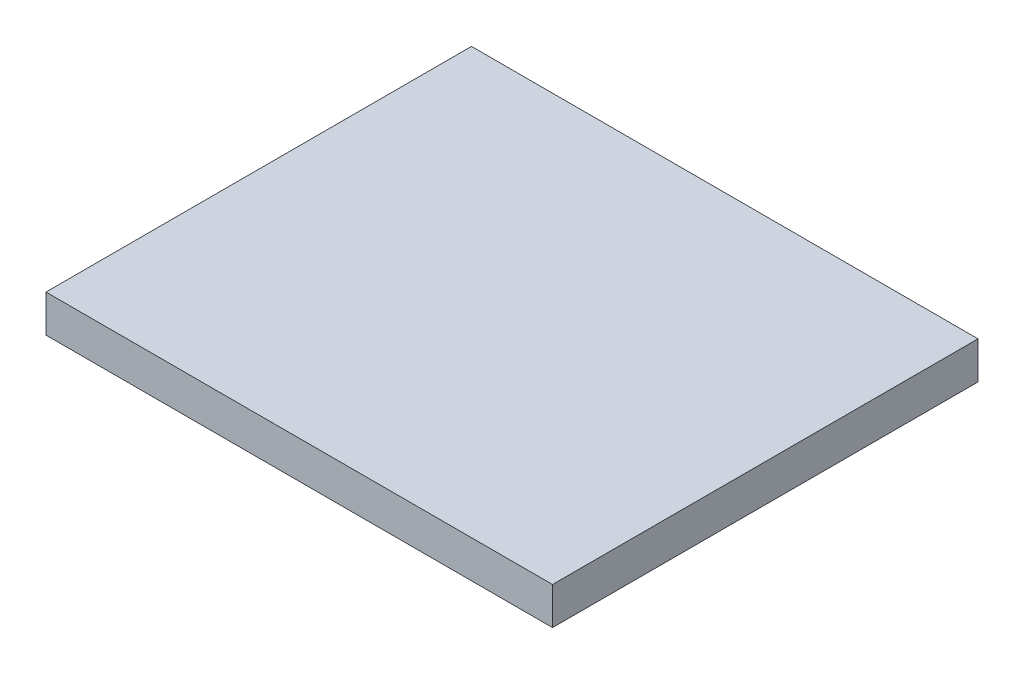
SolidWorks part; units mm, degrees
ref_plane "Front" through (0, 0, 0) normal (0, 0, 1) x (1, 0, 0)
ref_plane "Top" through (0, 0, 0) normal (0, 1, 0) x (1, 0, 0)
ref_plane "Right" through (0, 0, 0) normal (1, 0, 0) x (0, 0, -1)
sketch "Sketch1" plane through (0, 0, 0) normal (0, 1, 0) x (1, 0, 0)
  line L1 (-62.5, -52.5) -> (62.5, -52.5)
  line L2 (-62.5, -52.5) -> (-62.5, 52.5)
  line L3 (-62.5, 52.5) -> (62.5, 52.5)
  line L4 (62.5, -52.5) -> (62.5, 52.5)
  line L5 (-62.5, -52.5) -> (62.5, 52.5) construction
  line L6 (-62.5, 52.5) -> (62.5, -52.5) construction
  point P0 (0, 0)
  dimension "D1" = 125
  dimension "D2" = 105
extrude "Test_Base_Postion" add sketch "Sketch1" along normal blind 9.215
sketch "Thumb_Position" plane through (0, 9.215, 0) normal (0, 1, 0) x (1, 0, 0)
  line L0 (62.5, -52.5) -> (62.5, 52.5) construction
  line L1 (49, -12) -> (17, -12)
  line L2 (49, -12) -> (49, 43)
  line L3 (49, 43) -> (17, 43)
  line L4 (17, -12) -> (17, 43)
  line L5 (33, 43) -> (33, -12) construction
  line L6 (51, -12) -> (15, -12)
  line L7 (51, -12) -> (51, 12)
  line L8 (51, 12) -> (15, 12)
  line L9 (15, -12) -> (15, 12)
  line L10 (33, 12) -> (33, -12) construction
  line L12 (51, 0) -> (15, 0) construction
  circle A1 centre (42, 0) radius 9
  circle A2 centre (42, 0) radius 17.75 construction
  dimension "D6" = 18
  dimension "D7" = 20.5
  dimension "D5" = 35.5
  dimension "D1" = 55
  dimension "D2" = 32
  dimension "D3" = 36
  dimension "D4" = 24
sketch "Finger_Gears_Position" plane through (0, 0, 0) normal (0, -1, 0) x (1, 0, 0)
  line L0 (-30, 32) -> (-30, 49.5) construction
  line L1 (-30, 32) -> (-47.5, 32) construction
  line L2 (-30, -32) -> (-30, -49.5) construction
  line L3 (-30, -32) -> (-47.5, -32) construction
  line L4 (-62.5, -52.5) -> (-62.5, 52.5) construction
  line L5 (-62.5, 52.5) -> (62.5, 52.5) construction
  line L8 (62.5, -52.5) -> (-62.5, -52.5) construction
  line L9 (-62.5, 0) -> (62.5, 0) construction
  line L10 (62.5, 52.5) -> (62.5, -52.5) construction
  line L13 (-30, -32) -> (-43, -32) construction
  line L15 (-43, -48) -> (12, -48) construction
  line L16 (-43, -48) -> (-43, -16) construction
  line L17 (-43, -16) -> (12, -16) construction
  line L18 (12, -48) -> (12, -16) construction
  line L20 (-30, 32) -> (-43, 32) construction
  line L21 (12, -32) -> (-23, -32) construction
  line L22 (-43, 16) -> (12, 16) construction
  line L23 (-43, 16) -> (-43, 48) construction
  line L24 (-43, 48) -> (12, 48) construction
  line L25 (12, 16) -> (12, 48) construction
  line L26 (12, 32) -> (-23, 32) construction
  line L27 (-23, -32) -> (-23, 32) construction
  circle A0 centre (-30, 32) radius 17.5 construction
  circle A1 centre (-30, -32) radius 17.5 construction
  dimension "D1" = 35
  dimension "D2" = 15
  dimension "D3" = 3
  dimension "D4" = 3
  dimension "D5" = 13
  dimension "D6" = 55
  dimension "D7" = 32
  dimension "D8" = 13
  dimension "D9" = 55
  dimension "D10" = 32
  dimension "D11" = 35
  dimension "D12" = 35
sketch "Fingers_Position" plane through (0, 9.215, 0) normal (0, 1, 0) x (1, 0, 0)
  line L0 (12, 32) -> (-23, 32) construction
  line L1 (12, 16) -> (-43, 16)
  line L2 (12, 16) -> (12, 48)
  line L3 (12, 48) -> (-43, 48)
  line L4 (-43, 16) -> (-43, 48)
  line L5 (12, -48) -> (-43, -48)
  line L6 (12, -48) -> (12, -16)
  line L7 (12, -16) -> (-43, -16)
  line L8 (-43, -48) -> (-43, -16)
  line L9 (-23, 32) -> (-23, -32) construction
  line L10 (-23, -32) -> (12, -32) construction
sketch "Thumb_Knuckle_Mount_Position" plane through (0, 0, 0) normal (0, -1, 0) x (1, 0, 0)
  circle A0 centre (42, 0) radius 17.75
  dimension "D1" = 35.5
sketch "Gears_Position" plane through (0, 0, 0) normal (0, -1, 0) x (-1, 0, 0)
  line L0 (30, 32) -> (30, 13.5) construction
  line L1 (30, 32) -> (30.5905, 16.5113) construction
  line L2 (30.7851, 15.5187) -> (29.2149, 15.5187) construction
  line L3 (31.4977, 13.5607) -> (30, 17.6757) construction
  line L4 (28.2415, 13.5838) -> (30, 32) construction
  line L5 (29.2149, 15.5187) -> (27.6518, 15.6679) construction
  line L6 (30, -32) -> (30, -50.5) construction
  line L7 (30.7851, -48.4813) -> (29.2149, -48.4813) construction
  line L8 (30.5905, -47.4887) -> (30, -32) construction
  line L9 (31.4977, -50.4393) -> (30, -46.3243) construction
  line L10 (30, -32) -> (28.2415, -50.4162) construction
  line L11 (29.2149, -48.4813) -> (27.6518, -48.3321) construction
  line L12 (47.5, 2.2754) -> (47.5, -12.2246) construction
  line L13 (47.5, 2.2754) -> (48.0842, -9.2098) construction
  line L14 (48.2849, -10.1999) -> (46.7151, -10.1999) construction
  line L15 (48.9937, -12.1475) -> (47.5, -8.0435) construction
  line L16 (47.5, 2.2754) -> (45.6827, -12.1103) construction
  line L17 (46.7151, -10.1999) -> (45.1577, -10.0032) construction
  line L18 (19.3829, -13.0418) -> (17.8132, -13.0418) construction
  line L19 (18.5981, -0.5664) -> (16.7807, -14.9521) construction
  line L20 (17.8132, -13.0418) -> (16.2558, -12.845) construction
  line L21 (18.5981, -0.5664) -> (18.5981, -15.0664) construction
  line L22 (18.5981, -0.5664) -> (19.1823, -12.0516) construction
  line L23 (20.0918, -14.9893) -> (18.5981, -10.8853) construction
  line L24 (-8.6772, -11.927) -> (33.5, -2.2788) construction
  line L25 (16.0694, 14.2189) -> (8.7534, -28.4247) construction
  line L26 (-8.6772, -11.927) -> (16.0694, 14.2189) construction
  line L27 (-8.6772, -11.927) -> (8.7534, -28.4247) construction
  line L28 (8.7534, -28.4247) -> (33.5, -2.2788) construction
  line L29 (16.0694, 14.2189) -> (33.5, -2.2788) construction
  line L30 (12.4114, -7.1029) -> (24.7847, 5.97) construction
  line L31 (62.5, 52.5) -> (62.5, -52.5) construction
  circle A0 centre (30, -32) radius 17.5 construction
  circle A1 centre (30, 32) radius 17.5 construction
  circle A2 centre (30, 32) radius 16.5
  circle A3 centre (30, 32) radius 15.5 construction
  circle A4 centre (30, 32) radius 18.5 construction
  arc A5 (32.4899, 13.6683) -> (30.5905, 16.5113) centre (33.854, 16.6357) cw
  arc A6 (27.5101, 13.6683) -> (29.4095, 16.5113) centre (26.146, 16.6357) ccw
  arc A7 (32.4899, -50.3317) -> (30.5905, -47.4887) centre (33.854, -47.3643) cw
  arc A8 (27.5101, -50.3317) -> (29.4095, -47.4887) centre (26.146, -47.3643) ccw
  circle A9 centre (30, -32) radius 16.5
  circle A10 centre (30, -32) radius 18.5 construction
  circle A11 centre (30, -32) radius 15.5 construction
  arc A12 (28.9757, -50.4716) -> (27.6486, -47.3206) centre (30.8766, -47.816) cw
  arc A13 (24.0858, -49.5292) -> (26.4889, -47.0971) centre (23.3079, -46.3573) ccw
  arc A14 (25.4984, -49.944) -> (24.7916, -46.5987) centre (27.8676, -47.6961) cw
  arc A15 (20.8752, -48.0931) -> (23.6952, -46.1598) centre (20.7117, -44.8314) ccw
  arc A16 (22.1838, -48.7678) -> (22.1229, -45.3492) centre (24.9356, -47.0089) cw
  arc A17 (17.9945, -46.0754) -> (21.1294, -44.7107) centre (18.4512, -42.8417) ccw
  arc A18 (19.1518, -46.9855) -> (19.7389, -43.6172) centre (22.1867, -45.7792) cw
  arc A19 (15.5476, -43.549) -> (18.8842, -42.8022) centre (16.6081, -40.4601) ccw
  arc A20 (16.5118, -44.6617) -> (17.7258, -41.4654) centre (19.7201, -44.0516) cw
  arc A21 (13.6232, -40.6052) -> (17.0407, -40.5033) centre (15.2491, -37.7728) ccw
  arc A22 (14.3593, -41.8802) -> (16.1562, -38.9714) centre (17.6251, -41.8883) cw
  arc A23 (12.2906, -37.3503) -> (15.6656, -37.8971) centre (14.4231, -34.8769) ccw
  arc A24 (12.7721, -38.7416) -> (15.0871, -36.2255) centre (15.9774, -39.3676) cw
  arc A25 (11.598, -33.9021) -> (14.8086, -35.0777) centre (14.1602, -31.8769) ccw
  arc A26 (11.8076, -35.3594) -> (14.5569, -33.3268) centre (14.8365, -36.5807) cw
  arc A27 (11.5706, -30.3851) -> (14.5007, -32.1471) centre (14.4697, -28.8814) ccw
  arc A28 (11.5006, -31.8557) -> (14.5849, -30.3802) centre (14.2436, -33.6282) cw
  arc A29 (12.2093, -26.9265) -> (14.7529, -29.2112) centre (15.3405, -25.9987) ccw
  arc A30 (11.8622, -28.3573) -> (15.17, -27.4922) centre (14.2202, -30.6169) cw
  arc A31 (13.4909, -23.6513) -> (15.5563, -26.3761) centre (16.7412, -23.3328) ccw
  arc A32 (12.8793, -24.9905) -> (16.2911, -24.767) centre (14.7671, -27.6555) cw
  arc A33 (15.3693, -20.6778) -> (16.8816, -23.7442) centre (18.6211, -20.9802) ccw
  arc A34 (14.5153, -21.8771) -> (17.9077, -22.3033) centre (15.8646, -24.8512) cw
  arc A35 (17.7764, -18.1135) -> (18.6811, -21.4107) centre (20.9122, -19.0259) ccw
  arc A36 (16.7109, -19.1295) -> (19.9613, -20.1901) centre (17.473, -22.3052) cw
  arc A37 (20.6253, -16.0511) -> (20.8897, -19.46) centre (23.5318, -17.5404) ccw
  arc A38 (19.3868, -16.8471) -> (22.3778, -18.5036) centre (19.5341, -20.1096) cw
  arc A39 (23.8131, -14.5652) -> (23.4275, -17.9625) centre (26.3852, -16.5776) ccw
  arc A40 (22.4463, -15.1124) -> (25.0697, -17.305) centre (21.9735, -18.3438) cw
  arc A41 (27.2245, -13.7094) -> (26.2029, -16.9723) centre (29.3693, -16.1722) ccw
  arc A42 (25.7788, -13.988) -> (27.9399, -16.6375) centre (24.703, -17.0716) cw
  arc A43 (30.7361, -13.5147) -> (29.1155, -16.5253) centre (32.3761, -16.3389) ccw
  arc A44 (29.2639, -13.5147) -> (30.8845, -16.5253) centre (27.6239, -16.3389) cw
  arc A45 (34.2212, -13.988) -> (32.0601, -16.6375) centre (35.297, -17.0716) ccw
  arc A46 (32.7755, -13.7094) -> (33.7971, -16.9723) centre (30.6307, -16.1722) cw
  arc A47 (37.5537, -15.1124) -> (34.9303, -17.305) centre (38.0265, -18.3438) ccw
  arc A48 (36.1869, -14.5652) -> (36.5725, -17.9625) centre (33.6148, -16.5776) cw
  arc A49 (40.6132, -16.8471) -> (37.6222, -18.5036) centre (40.4659, -20.1096) ccw
  arc A50 (39.3747, -16.0511) -> (39.1103, -19.46) centre (36.4682, -17.5404) cw
  arc A51 (43.2891, -19.1295) -> (40.0387, -20.1901) centre (42.527, -22.3052) ccw
  arc A52 (42.2236, -18.1135) -> (41.3189, -21.4107) centre (39.0878, -19.0259) cw
  arc A53 (45.4847, -21.8771) -> (42.0923, -22.3033) centre (44.1354, -24.8512) ccw
  arc A54 (44.6307, -20.6778) -> (43.1184, -23.7442) centre (41.3789, -20.9802) cw
  arc A55 (47.1207, -24.9905) -> (43.7089, -24.767) centre (45.2329, -27.6555) ccw
  arc A56 (46.5091, -23.6513) -> (44.4437, -26.3761) centre (43.2588, -23.3328) cw
  arc A57 (48.1378, -28.3573) -> (44.83, -27.4922) centre (45.7798, -30.6169) ccw
  arc A58 (47.7907, -26.9265) -> (45.2471, -29.2112) centre (44.6595, -25.9987) cw
  arc A59 (48.4994, -31.8557) -> (45.4151, -30.3802) centre (45.7564, -33.6282) ccw
  arc A60 (48.4294, -30.3851) -> (45.4993, -32.1471) centre (45.5303, -28.8814) cw
  arc A61 (48.1924, -35.3594) -> (45.4431, -33.3268) centre (45.1635, -36.5807) ccw
  arc A62 (48.402, -33.9021) -> (45.1914, -35.0777) centre (45.8398, -31.8769) cw
  arc A63 (47.2279, -38.7416) -> (44.9129, -36.2255) centre (44.0226, -39.3676) ccw
  arc A64 (47.7094, -37.3503) -> (44.3344, -37.8971) centre (45.5769, -34.8769) cw
  arc A65 (45.6407, -41.8802) -> (43.8438, -38.9714) centre (42.3749, -41.8883) ccw
  arc A66 (46.3768, -40.6052) -> (42.9593, -40.5033) centre (44.7509, -37.7728) cw
  arc A67 (43.4882, -44.6617) -> (42.2742, -41.4654) centre (40.2799, -44.0516) ccw
  arc A68 (44.4524, -43.549) -> (41.1158, -42.8022) centre (43.3919, -40.4601) cw
  arc A69 (40.8482, -46.9855) -> (40.2611, -43.6172) centre (37.8133, -45.7792) ccw
  arc A70 (42.0055, -46.0754) -> (38.8706, -44.7107) centre (41.5488, -42.8417) cw
  arc A71 (37.8162, -48.7678) -> (37.8771, -45.3492) centre (35.0644, -47.0089) ccw
  arc A72 (39.1248, -48.0931) -> (36.3048, -46.1598) centre (39.2883, -44.8314) cw
  arc A73 (34.5016, -49.944) -> (35.2084, -46.5987) centre (32.1324, -47.6961) ccw
  arc A74 (35.9142, -49.5292) -> (33.5111, -47.0971) centre (36.6921, -46.3573) cw
  arc A75 (31.0243, -50.4716) -> (32.3514, -47.3206) centre (29.1234, -47.816) ccw
  arc A76 (28.9757, 13.5284) -> (27.6486, 16.6794) centre (30.8766, 16.184) cw
  arc A77 (24.0858, 14.4708) -> (26.4889, 16.9029) centre (23.3079, 17.6427) ccw
  arc A78 (25.4984, 14.056) -> (24.7916, 17.4013) centre (27.8676, 16.3039) cw
  arc A79 (20.8752, 15.9069) -> (23.6952, 17.8402) centre (20.7117, 19.1686) ccw
  arc A80 (22.1838, 15.2322) -> (22.1229, 18.6508) centre (24.9356, 16.9911) cw
  arc A81 (17.9945, 17.9246) -> (21.1294, 19.2893) centre (18.4512, 21.1583) ccw
  arc A82 (19.1518, 17.0145) -> (19.7389, 20.3828) centre (22.1867, 18.2208) cw
  arc A83 (15.5476, 20.451) -> (18.8842, 21.1978) centre (16.6081, 23.5399) ccw
  arc A84 (16.5118, 19.3383) -> (17.7258, 22.5346) centre (19.7201, 19.9484) cw
  arc A85 (13.6232, 23.3948) -> (17.0407, 23.4967) centre (15.2491, 26.2272) ccw
  arc A86 (14.3593, 22.1198) -> (16.1562, 25.0286) centre (17.6251, 22.1117) cw
  arc A87 (12.2906, 26.6497) -> (15.6656, 26.1029) centre (14.4231, 29.1231) ccw
  arc A88 (12.7721, 25.2584) -> (15.0871, 27.7745) centre (15.9774, 24.6324) cw
  arc A89 (11.598, 30.0979) -> (14.8086, 28.9223) centre (14.1602, 32.1231) ccw
  arc A90 (11.8076, 28.6406) -> (14.5569, 30.6732) centre (14.8365, 27.4193) cw
  arc A91 (11.5706, 33.6149) -> (14.5007, 31.8529) centre (14.4697, 35.1186) ccw
  arc A92 (11.5006, 32.1443) -> (14.5849, 33.6198) centre (14.2436, 30.3718) cw
  arc A93 (12.2093, 37.0735) -> (14.7529, 34.7888) centre (15.3405, 38.0013) ccw
  arc A94 (11.8622, 35.6427) -> (15.17, 36.5078) centre (14.2202, 33.3831) cw
  arc A95 (13.4909, 40.3487) -> (15.5563, 37.6239) centre (16.7412, 40.6672) ccw
  arc A96 (12.8793, 39.0095) -> (16.2911, 39.233) centre (14.7671, 36.3445) cw
  arc A97 (15.3693, 43.3222) -> (16.8816, 40.2558) centre (18.6211, 43.0198) ccw
  arc A98 (14.5153, 42.1229) -> (17.9077, 41.6967) centre (15.8646, 39.1488) cw
  arc A99 (17.7764, 45.8865) -> (18.6811, 42.5893) centre (20.9122, 44.9741) ccw
  arc A100 (16.7109, 44.8705) -> (19.9613, 43.8099) centre (17.473, 41.6948) cw
  arc A101 (20.6253, 47.9489) -> (20.8897, 44.54) centre (23.5318, 46.4596) ccw
  arc A102 (19.3868, 47.1529) -> (22.3778, 45.4964) centre (19.5341, 43.8904) cw
  arc A103 (23.8131, 49.4348) -> (23.4275, 46.0375) centre (26.3852, 47.4224) ccw
  arc A104 (22.4463, 48.8876) -> (25.0697, 46.695) centre (21.9735, 45.6562) cw
  arc A105 (27.2245, 50.2906) -> (26.2029, 47.0277) centre (29.3693, 47.8278) ccw
  arc A106 (25.7788, 50.012) -> (27.9399, 47.3625) centre (24.703, 46.9284) cw
  arc A107 (30.7361, 50.4853) -> (29.1155, 47.4747) centre (32.3761, 47.6611) ccw
  arc A108 (29.2639, 50.4853) -> (30.8845, 47.4747) centre (27.6239, 47.6611) cw
  arc A109 (34.2212, 50.012) -> (32.0601, 47.3625) centre (35.297, 46.9284) ccw
  arc A110 (32.7755, 50.2906) -> (33.7971, 47.0277) centre (30.6307, 47.8278) cw
  arc A111 (37.5537, 48.8876) -> (34.9303, 46.695) centre (38.0265, 45.6562) ccw
  arc A112 (36.1869, 49.4348) -> (36.5725, 46.0375) centre (33.6148, 47.4224) cw
  arc A113 (40.6132, 47.1529) -> (37.6222, 45.4964) centre (40.4659, 43.8904) ccw
  arc A114 (39.3747, 47.9489) -> (39.1103, 44.54) centre (36.4682, 46.4596) cw
  arc A115 (43.2891, 44.8705) -> (40.0387, 43.8099) centre (42.527, 41.6948) ccw
  arc A116 (42.2236, 45.8865) -> (41.3189, 42.5893) centre (39.0878, 44.9741) cw
  arc A117 (45.4847, 42.1229) -> (42.0923, 41.6967) centre (44.1354, 39.1488) ccw
  arc A118 (44.6307, 43.3222) -> (43.1184, 40.2558) centre (41.3789, 43.0198) cw
  arc A119 (47.1207, 39.0095) -> (43.7089, 39.233) centre (45.2329, 36.3445) ccw
  arc A120 (46.5091, 40.3487) -> (44.4437, 37.6239) centre (43.2588, 40.6672) cw
  arc A121 (48.1378, 35.6427) -> (44.83, 36.5078) centre (45.7798, 33.3831) ccw
  arc A122 (47.7907, 37.0735) -> (45.2471, 34.7888) centre (44.6595, 38.0013) cw
  arc A123 (48.4994, 32.1443) -> (45.4151, 33.6198) centre (45.7564, 30.3718) ccw
  arc A124 (48.4294, 33.6149) -> (45.4993, 31.8529) centre (45.5303, 35.1186) cw
  arc A125 (48.1924, 28.6406) -> (45.4431, 30.6732) centre (45.1635, 27.4193) ccw
  arc A126 (48.402, 30.0979) -> (45.1914, 28.9223) centre (45.8398, 32.1231) cw
  arc A127 (47.2279, 25.2584) -> (44.9129, 27.7745) centre (44.0226, 24.6324) ccw
  arc A128 (47.7094, 26.6497) -> (44.3344, 26.1029) centre (45.5769, 29.1231) cw
  arc A129 (45.6407, 22.1198) -> (43.8438, 25.0286) centre (42.3749, 22.1117) ccw
  arc A130 (46.3768, 23.3948) -> (42.9593, 23.4967) centre (44.7509, 26.2272) cw
  arc A131 (43.4882, 19.3383) -> (42.2742, 22.5346) centre (40.2799, 19.9484) ccw
  arc A132 (44.4524, 20.451) -> (41.1158, 21.1978) centre (43.3919, 23.5399) cw
  arc A133 (40.8482, 17.0145) -> (40.2611, 20.3828) centre (37.8133, 18.2208) ccw
  arc A134 (42.0055, 17.9246) -> (38.8706, 19.2893) centre (41.5488, 21.1583) cw
  arc A135 (37.8162, 15.2322) -> (37.8771, 18.6508) centre (35.0644, 16.9911) ccw
  arc A136 (39.1248, 15.9069) -> (36.3048, 17.8402) centre (39.2883, 19.1686) cw
  arc A137 (34.5016, 14.056) -> (35.2084, 17.4013) centre (32.1324, 16.3039) ccw
  arc A138 (35.9142, 14.4708) -> (33.5111, 16.9029) centre (36.6921, 17.6427) cw
  arc A139 (31.0243, 13.5284) -> (32.3514, 16.6794) centre (29.1234, 16.184) ccw
  circle A140 centre (47.5, 2.2754) radius 11.5 construction
  circle A141 centre (47.5, 2.2754) radius 12.5
  circle A142 centre (47.5, 2.2754) radius 13.5 construction
  circle A143 centre (47.5, 2.2754) radius 14.5 construction
  arc A144 (49.8668, -12.0301) -> (48.0842, -9.2098) centre (51.48, -9.037) cw
  arc A145 (45.1332, -12.0301) -> (46.9158, -9.2098) centre (43.52, -9.037) ccw
  arc A146 (16.2312, -14.872) -> (18.0138, -12.0516) centre (14.6181, -11.8789) ccw
  circle A147 centre (18.5981, -0.5664) radius 11.5 construction
  circle A148 centre (18.5981, -0.5664) radius 12.5
  arc A149 (20.9649, -14.872) -> (19.1823, -12.0516) centre (22.578, -11.8789) cw
  circle A150 centre (18.5981, -0.5664) radius 13.5 construction
  circle A151 centre (18.5981, -0.5664) radius 14.5 construction
  arc A152 (46.2348, -12.1693) -> (45.2096, -8.9942) centre (48.5416, -9.6714) cw
  arc A153 (41.6499, -10.9921) -> (44.0779, -8.7036) centre (40.8318, -7.6919) ccw
  arc A154 (42.6823, -11.4009) -> (42.4789, -8.0706) centre (45.5379, -9.5551) cw
  arc A155 (38.5342, -9.1204) -> (41.455, -7.5077) centre (38.5625, -5.7204) ccw
  arc A156 (39.4325, -9.7731) -> (40.0638, -6.4969) centre (42.6574, -8.6955) cw
  arc A157 (35.9819, -6.5327) -> (39.212, -5.697) centre (36.8548, -3.2465) ccw
  arc A158 (36.6896, -7.3883) -> (38.1158, -4.3719) centre (40.0812, -7.1465) cw
  arc A159 (34.1532, -3.3915) -> (37.4897, -3.3854) centre (35.816, -0.4257) ccw
  arc A160 (34.626, -4.3962) -> (36.7575, -1.8293) centre (37.9711, -5.0055) cw
  arc A161 (33.1632, 0.1057) -> (36.3964, -0.7181) centre (35.5114, 2.5648) ccw
  arc A162 (33.3713, -0.985) -> (36.0742, 0.9712) centre (36.4598, -2.407) cw
  arc A163 (33.0741, 3.7393) -> (36.0008, 2.1373) centre (35.96, 5.5372) ccw
  arc A164 (33.0044, 2.6311) -> (36.1088, 3.8536) centre (35.6422, 0.4857) cw
  arc A165 (33.8914, 7.2809) -> (36.3278, 5.0014) centre (37.1337, 8.3046) ccw
  arc A166 (33.5482, 6.2248) -> (36.8592, 6.6369) centre (35.5696, 3.4908) cw
  arc A167 (35.5637, 10.508) -> (37.3567, 7.6941) centre (38.9588, 10.6932) ccw
  arc A168 (34.9687, 9.5704) -> (38.2781, 9.1462) centre (36.2467, 6.4196) cw
  arc A169 (37.9861, 13.2177) -> (39.0229, 10.0464) centre (41.3206, 12.5528) ccw
  arc A170 (37.1766, 12.4576) -> (40.2766, 11.2237) centre (37.6309, 9.088) cw
  arc A171 (41.0062, 15.24) -> (41.2218, 11.9105) centre (44.0706, 13.7667) ccw
  arc A172 (40.0332, 14.705) -> (42.7288, 12.7389) centre (39.6351, 11.3283) cw
  arc A173 (44.4344, 16.4476) -> (43.8152, 13.1691) centre (47.0361, 14.2585) ccw
  arc A174 (43.3589, 16.1715) -> (45.4809, 13.5968) centre (42.1336, 12.9998) cw
  arc A175 (48.0552, 16.7648) -> (46.6401, 13.7432) centre (50.0308, 13.9974) ccw
  arc A176 (46.9448, 16.7648) -> (48.3599, 13.7432) centre (44.9692, 13.9974) cw
  arc A177 (51.6411, 16.1715) -> (49.5191, 13.5968) centre (52.8664, 12.9998) ccw
  arc A178 (50.5656, 16.4476) -> (51.1848, 13.1691) centre (47.9639, 14.2585) cw
  arc A179 (54.9668, 14.705) -> (52.2712, 12.7389) centre (55.3649, 11.3283) ccw
  arc A180 (53.9938, 15.24) -> (53.7782, 11.9105) centre (50.9294, 13.7667) cw
  arc A181 (57.8234, 12.4576) -> (54.7234, 11.2237) centre (57.3691, 9.088) ccw
  arc A182 (57.0139, 13.2177) -> (55.9771, 10.0464) centre (53.6794, 12.5528) cw
  arc A183 (60.0313, 9.5704) -> (56.7219, 9.1462) centre (58.7533, 6.4196) ccw
  arc A184 (59.4363, 10.508) -> (57.6433, 7.6941) centre (56.0412, 10.6932) cw
  arc A185 (61.4518, 6.2248) -> (58.1408, 6.6369) centre (59.4304, 3.4908) ccw
  arc A186 (61.1086, 7.2809) -> (58.6722, 5.0014) centre (57.8663, 8.3046) cw
  arc A187 (61.9956, 2.6311) -> (58.8912, 3.8536) centre (59.3578, 0.4857) ccw
  arc A188 (61.9259, 3.7393) -> (58.9992, 2.1373) centre (59.04, 5.5372) cw
  arc A189 (61.6287, -0.985) -> (58.9258, 0.9712) centre (58.5402, -2.407) ccw
  arc A190 (61.8368, 0.1057) -> (58.6036, -0.7181) centre (59.4886, 2.5648) cw
  arc A191 (60.374, -4.3962) -> (58.2425, -1.8293) centre (57.0289, -5.0055) ccw
  arc A192 (60.8468, -3.3915) -> (57.5103, -3.3854) centre (59.184, -0.4257) cw
  arc A193 (58.3104, -7.3883) -> (56.8842, -4.3719) centre (54.9188, -7.1465) ccw
  arc A194 (59.0181, -6.5327) -> (55.788, -5.697) centre (58.1452, -3.2465) cw
  arc A195 (55.5675, -9.7731) -> (54.9362, -6.4969) centre (52.3426, -8.6955) ccw
  arc A196 (56.4658, -9.1204) -> (53.545, -7.5077) centre (56.4375, -5.7204) cw
  arc A197 (52.3177, -11.4009) -> (52.5211, -8.0706) centre (49.4621, -9.5551) ccw
  arc A198 (53.3501, -10.9921) -> (50.9221, -8.7036) centre (54.1682, -7.6919) cw
  arc A199 (48.7652, -12.1693) -> (49.7904, -8.9942) centre (46.4584, -9.6714) ccw
  arc A200 (12.748, -13.8339) -> (15.176, -11.5455) centre (11.9299, -10.5337) ccw
  arc A201 (17.3329, -15.0111) -> (16.3077, -11.836) centre (19.6397, -12.5132) cw
  arc A202 (9.6323, -11.9622) -> (12.5531, -10.3495) centre (9.6606, -8.5622) ccw
  arc A203 (13.7804, -14.2427) -> (13.577, -10.9124) centre (16.6359, -12.3969) cw
  arc A204 (7.0799, -9.3745) -> (10.3101, -8.5388) centre (7.9529, -6.0884) ccw
  arc A205 (10.5306, -12.6149) -> (11.1618, -9.3387) centre (13.7555, -11.5373) cw
  arc A206 (5.2513, -6.2333) -> (8.5878, -6.2272) centre (6.9141, -3.2675) ccw
  arc A207 (7.7877, -10.2301) -> (9.2139, -7.2138) centre (11.1792, -9.9883) cw
  arc A208 (4.2613, -2.7361) -> (7.4945, -3.5599) centre (6.6094, -0.277) ccw
  arc A209 (5.7241, -7.2381) -> (7.8556, -4.6712) centre (9.0692, -7.8473) cw
  arc A210 (4.1722, 0.8975) -> (7.0989, -0.7045) centre (7.0581, 2.6954) ccw
  arc A211 (4.4694, -3.8268) -> (7.1723, -1.8707) centre (7.5579, -5.2489) cw
  arc A212 (4.9894, 4.4391) -> (7.4258, 2.1595) centre (8.2318, 5.4628) ccw
  arc A213 (4.1024, -0.2107) -> (7.2069, 1.0118) centre (6.7402, -2.3562) cw
  arc A214 (6.6618, 7.6661) -> (8.4547, 4.8523) centre (10.0569, 7.8513) ccw
  arc A215 (4.6463, 3.383) -> (7.9572, 3.7951) centre (6.6677, 0.649) cw
  arc A216 (9.0841, 10.3759) -> (10.121, 7.2046) centre (12.4186, 9.711) ccw
  arc A217 (6.0668, 6.7286) -> (9.3762, 6.3043) centre (7.3448, 3.5778) cw
  arc A218 (12.1043, 12.3982) -> (12.3199, 9.0686) centre (15.1687, 10.9249) ccw
  arc A219 (8.2747, 9.6158) -> (11.3746, 8.3819) centre (8.7289, 6.2461) cw
  arc A220 (15.5325, 13.6058) -> (14.9133, 10.3273) centre (18.1342, 11.4167) ccw
  arc A221 (11.1312, 11.8632) -> (13.8269, 9.8971) centre (10.7332, 8.4865) cw
  arc A222 (19.1533, 13.9229) -> (17.7382, 10.9014) centre (21.1288, 11.1556) ccw
  arc A223 (14.4569, 13.3296) -> (16.579, 10.7549) centre (13.2317, 10.158) cw
  arc A224 (22.7392, 13.3296) -> (20.6171, 10.7549) centre (23.9645, 10.158) ccw
  arc A225 (18.0429, 13.9229) -> (19.4579, 10.9014) centre (16.0673, 11.1556) cw
  arc A226 (26.0649, 11.8632) -> (23.3692, 9.8971) centre (26.4629, 8.4865) ccw
  arc A227 (21.6637, 13.6058) -> (22.2828, 10.3273) centre (19.062, 11.4167) cw
  arc A228 (28.9214, 9.6158) -> (25.8215, 8.3819) centre (28.4672, 6.2461) ccw
  arc A229 (25.0918, 12.3982) -> (24.8762, 9.0686) centre (22.0275, 10.9249) cw
  arc A230 (31.1293, 6.7286) -> (27.8199, 6.3043) centre (29.8514, 3.5778) ccw
  arc A231 (28.112, 10.3759) -> (27.0751, 7.2046) centre (24.7775, 9.711) cw
  arc A232 (32.5498, 3.383) -> (29.2389, 3.7951) centre (30.5284, 0.649) ccw
  arc A233 (30.5343, 7.6661) -> (28.7414, 4.8523) centre (27.1393, 7.8513) cw
  arc A234 (33.0937, -0.2107) -> (29.9893, 1.0118) centre (30.4559, -2.3562) ccw
  arc A235 (32.2067, 4.4391) -> (29.7703, 2.1595) centre (28.9643, 5.4628) cw
  arc A236 (32.7268, -3.8268) -> (30.0239, -1.8707) centre (29.6383, -5.2489) ccw
  arc A237 (33.024, 0.8975) -> (30.0972, -0.7045) centre (30.1381, 2.6954) cw
  arc A238 (31.472, -7.2381) -> (29.3406, -4.6712) centre (28.1269, -7.8473) ccw
  arc A239 (32.9348, -2.7361) -> (29.7016, -3.5599) centre (30.5867, -0.277) cw
  arc A240 (29.4084, -10.2301) -> (27.9823, -7.2138) centre (26.0169, -9.9883) ccw
  arc A241 (31.9448, -6.2333) -> (28.6083, -6.2272) centre (30.282, -3.2675) cw
  arc A242 (26.6655, -12.6149) -> (26.0343, -9.3387) centre (23.4407, -11.5373) ccw
  arc A243 (30.1162, -9.3745) -> (26.8861, -8.5388) centre (29.2432, -6.0884) cw
  arc A244 (23.4157, -14.2427) -> (23.6191, -10.9124) centre (20.5602, -12.3969) ccw
  arc A245 (27.5639, -11.9622) -> (24.643, -10.3495) centre (27.5355, -8.5622) cw
  arc A246 (19.8632, -15.0111) -> (20.8884, -11.836) centre (17.5564, -12.5132) ccw
  arc A247 (24.4482, -13.8339) -> (22.0202, -11.5455) centre (25.2663, -10.5337) cw
  point P233 (30, -32)
  point P426 (30, 32)
  point P461 (12.4114, -7.1029)
  point P607 (47.5, 2.2754)
  point P608 (18.5981, -0.5664)
  point P609 (0, 0)
  point P753 (18.5981, -0.5664)
  point P754 (18.5981, -0.5664)
  point P759 (47.5, 7.1601)
  point P760 (47.5, 2.2754)
  dimension "D1" = 35
  dimension "D2" = 31
  dimension "D3" = 33
  dimension "D4" = 37
  dimension "D7" = 37
  dimension "D8" = 33
  dimension "D9" = 31
  dimension "D14" = 23
  dimension "D15" = 25
  dimension "D16" = 27
  dimension "D17" = 29
  dimension "D20" = 23
  dimension "D21" = 25
  dimension "D22" = 27
  dimension "D23" = 29
  dimension "D5" = 20
  dimension "D6" = 5.455
  dimension "D10" = 20
  dimension "D11" = 5.455
  dimension "D18" = 20
  dimension "D19" = 7.2
  dimension "D24" = 20
  dimension "D25" = 7.2
  dimension "D28" = 36
  dimension "D29" = 24
  dimension "D30" = 29
  dimension "D31" = 15
  dimension "D12" = 33
  dimension "D13" = 33
  dimension "D26" = 25
  dimension "D27" = 25
sketch "XL320_Position" plane through (0, 9.215, 0) normal (0, 1, 0) x (1, 0, 0)
  line L0 (0.062, 11.1823) -> (2.3378, -12.7095)
  line L1 (2.3378, -12.7095) -> (-33.5, -16.1231)
  line L2 (-33.5, -16.1231) -> (-35.7758, 7.7687)
  line L3 (-35.7758, 7.7687) -> (0.062, 11.1823)
equation "\"D6@Gears_Position\"=180/33"
equation "\"D11@Gears_Position\"=180/33"
equation "\"D19@Gears_Position\"=180/25"
